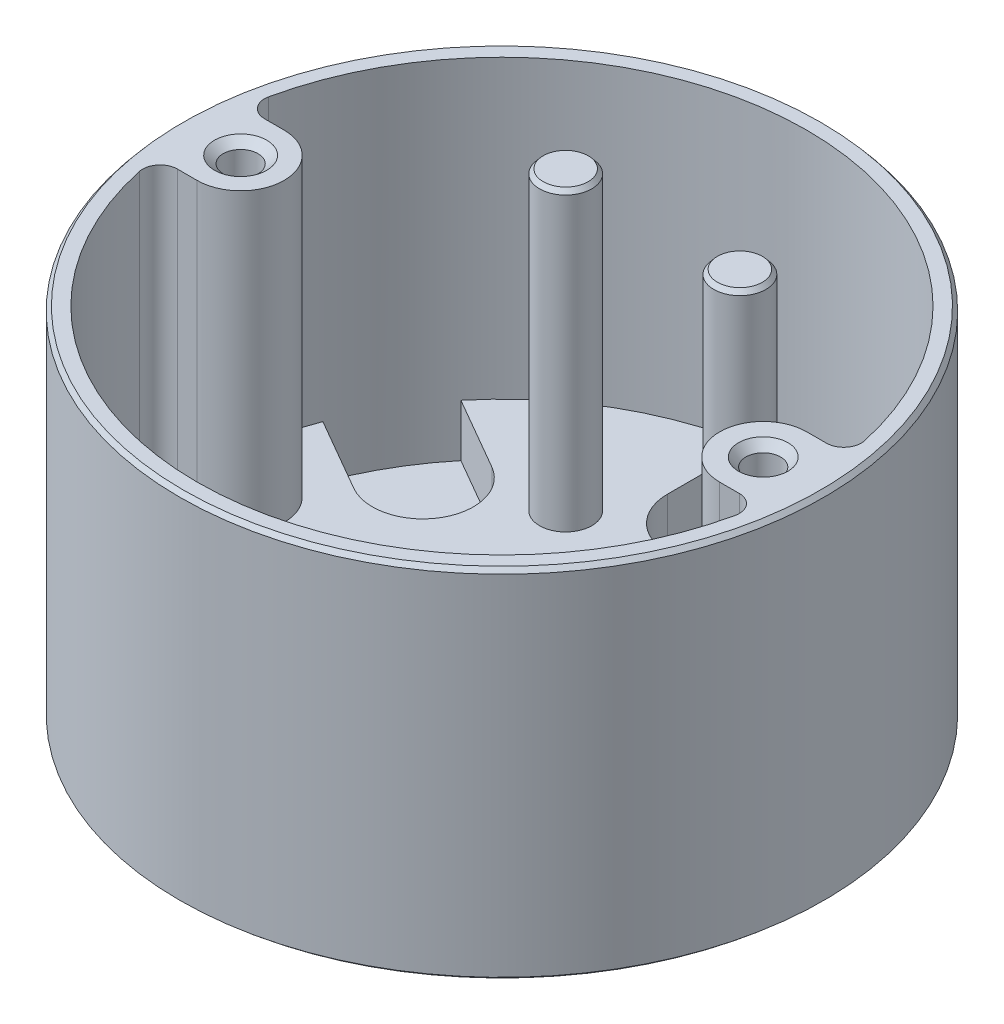
SolidWorks part; units mm, degrees
material "AISI 1020 Steel, Cold Rolled"
ref_plane "Front" through (0, 0, 0) normal (0, 0, 1) x (1, 0, 0)
ref_plane "Top" through (0, 0, 0) normal (0, 1, 0) x (1, 0, 0)
ref_plane "Right" through (0, 0, 0) normal (1, 0, 0) x (0, 0, -1)
sketch "Sketch1" plane through (0, 0, 0) normal (0, 1, 0) x (1, 0, 0)
  circle A0 centre (0, 0) radius 18.5
  dimension "D1" = 37
extrude "Boss-Extrude1" add sketch "Sketch1" along normal blind 20.5
sketch "Sketch2" plane through (0, 20.5, 0) normal (0, 1, 0) x (1, 0, 0)
  circle A0 centre (0, 0) radius 17.5
  dimension "D1" = 35
extrude "Cut-Extrude1" cut sketch "Sketch2" against normal blind 17
sketch "Sketch4" plane through (0, 0, 0) normal (0, -1, 0) x (1, 0, 0)
  circle A0 centre (0, 0) radius 5.25
  dimension "D1" = 10.5
extrude "Cut-Extrude2" cut sketch "Sketch4" against normal up to next
sketch "Sketch5" plane through (0, 3.5, 0) normal (0, 1, 0) x (1, 0, 0)
  line L0 (-15, 2.5) -> (-17.5, 2.5)
  line L1 (-17.5, 2.5) -> (-17.5, 0)
  line L2 (-17.5, 0) -> (-17.5, -2.5)
  line L3 (-17.5, -2.5) -> (-15, -2.5)
  circle A0 centre (-15, 0) radius 2.5
  circle M3 centre (0, 0) radius 17.5
  dimension "D2" = 5
  dimension "D1" = 15
extrude "Boss-Extrude2" add sketch "Sketch5" along normal up to surface (17 mm away) contours A0 | A0 L0 M3 | A0 L3 M3 up to face at (0, 20.5, 17.5)
fillet "Fillet1" radius 1 2 edges at (-17.3205, 12, 2.5) (-17.3205, 12, -2.5)
sketch "Sketch6" plane through (0, 20.5, 0) normal (0, 1, 0) x (1, 0, 0)
  circle A0 centre (-15, 0) radius 1
  arc A1 (-15, -2.5) -> (-15, 2.5) centre (-15, 0) ccw construction
  dimension "D1" = 2
extrude "Cut-Extrude3" cut sketch "Sketch6" against normal through all
mirror "Mirror1" about plane through (0, 0, 0) normal (1, 0, 0) of "Fillet1", "Boss-Extrude2", "Cut-Extrude3"
sketch "Sketch7" plane through (0, 3.5, 0) normal (0, 1, 0) x (1, 0, 0)
  line L0 (-2.9, 12.4) -> (-2.9, 17.258)
  line L1 (0, 12.4) -> (0, 9.5) construction
  line L2 (2.9, 17.258) -> (2.9, 12.4)
  line L3 (0, 17.5) -> (0, 20.4848) construction
  circle A0 centre (0, 12.4) radius 2.9
  arc A2 (-2.9, 17.258) -> (2.9, 17.258) centre (0, 0) cw
  arc A4 (17.1018, 3.7121) -> (-17.1018, 3.7121) centre (0, 0) ccw construction
  arc A5 (17.1018, 3.7121) -> (-17.1018, 3.7121) centre (0, 0) ccw construction
  arc M11 (17.1018, 3.7121) -> (-17.1018, 3.7121) centre (0, 0) ccw
  dimension "D2" = 8
  dimension "D1" = 5.8
extrude "Cut-Extrude4" cut sketch "Sketch7" against normal blind 3 contours A0 | A0 L2 L0 M11
pattern_circular "CirPattern1" count 6 over 360 about axis through (0, 0, 0) along (0, 1, 0) of "Cut-Extrude4"
sketch "Sketch8" plane through (0, 0, 0) normal (0, -1, 0) x (1, 0, 0)
  circle A0 centre (0, 0) radius 6.5
  dimension "D1" = 13
extrude "Cut-Extrude5" cut sketch "Sketch8" against normal blind 1
sketch "Sketch9" plane through (0, 0, 0) normal (0, -1, 0) x (1, 0, 0)
  line L0 (0, 0) -> (0, 3.6501) construction
  circle A0 centre (-8, 0) radius 1
  circle A1 centre (8, 0) radius 1
  dimension "D2" = 2
  dimension "D1" = 16
extrude "Cut-Extrude6" cut sketch "Sketch9" against normal up to next
sketch "Sketch11" plane through (0, 0.5, 0) normal (0, 1, 0) x (1, 0, 0)
  circle A0 centre (0, 12.5) radius 1.5
  dimension "D1" = 3
  dimension "D2" = 12.5
extrude "Cut-Extrude7" cut sketch "Sketch11" against normal up to next
pattern_circular "CirPattern2" count 3 over 360 about axis through (0, 0, 0) along (0, 1, 0) of "Cut-Extrude7"
sketch "Sketch12" plane through (0, 3.5, 0) normal (0, 1, 0) x (1, 0, 0)
  line L0 (-5, 8.6603) -> (5, 8.6603) construction
  circle A0 centre (-5, 8.6603) radius 1.5
  circle A1 centre (5, 8.6603) radius 1.5
  point P4 (-3.9685, 9.1789)
  dimension "D1" = 3
  dimension "D2" = 10
  dimension "D3" = 10
  dimension "D4" = 10
extrude "Boss-Extrude3" add sketch "Sketch12" along normal up to surface (17 mm away) up to face at (15, 20.5, 1)
chamfer "Chamfer1" distance 0.5 angle 40 2 edges at (15, 20.5, 1) (-15, 20.5, 1)
chamfer "Chamfer2" distance 0.25 angle 40 2 edges at (5, 20.5, -7.1603) (-5, 20.5, -7.1603)
chamfer "Chamfer3" distance 0.25 angle 40 2 edges at (0, 20.5, 18.5) (0, 0, 18.5)
